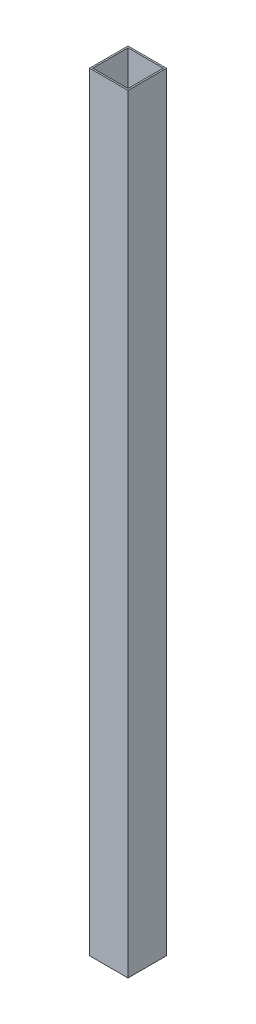
SolidWorks part; units mm, degrees
ref_plane "Front Plane" through (0, 0, 0) normal (0, 0, 1) x (1, 0, 0)
ref_plane "Top Plane" through (0, 0, 0) normal (0, 1, 0) x (1, 0, 0)
ref_plane "Right Plane" through (0, 0, 0) normal (1, 0, 0) x (0, 0, -1)
sketch "Sketch1" plane through (0, 0, 0) normal (0, 1, 0) x (1, 0, 0)
  line L0 (-23, 23) -> (23, 23)
  line L1 (-25, -25) -> (25, -25)
  line L2 (-25, -25) -> (-25, 25)
  line L3 (-25, 25) -> (25, 25)
  line L4 (25, -25) -> (25, 25)
  line L5 (-25, -25) -> (25, 25) construction
  line L6 (-25, 25) -> (25, -25) construction
  line L7 (23, -23) -> (23, 23)
  line L8 (-23, -23) -> (23, -23)
  line L9 (-23, -23) -> (-23, 23)
  point P0 (0, 0)
  dimension "D1" = 50
  dimension "D2" = 2
extrude "Boss-Extrude1" add sketch "Sketch1" along normal blind 1000
